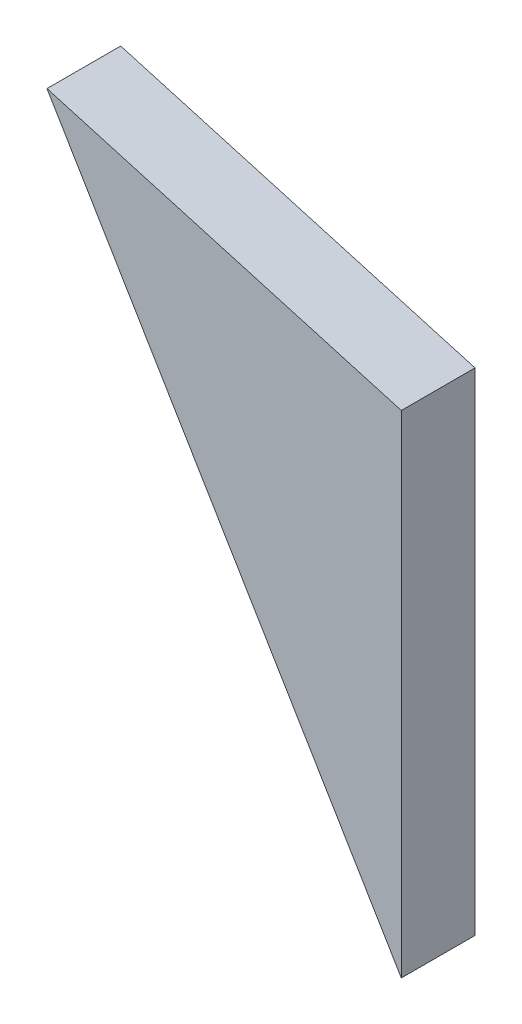
SolidWorks part; units mm, degrees
ref_plane "Front Plane" through (0, 0, 0) normal (0, 0, 1) x (1, 0, 0)
ref_plane "Top Plane" through (0, 0, 0) normal (0, 1, 0) x (1, 0, 0)
ref_plane "Right Plane" through (0, 0, 0) normal (1, 0, 0) x (0, 0, -1)
sketch "Sketch1" plane through (0, 0, 0) normal (0, 0, 1) x (1, 0, 0)
  line L0 (0, 0) -> (0, -20)
  line L1 (0, -20) -> (-14.4189, 4.1346)
  line L2 (-14.4189, 4.1346) -> (0, 0)
  line L3 (0, 0) -> (7.0215, 0) construction
  dimension "D1" = 16
  dimension "D2" = 20
  dimension "D3" = 15
extrude "Boss-Extrude1" add sketch "Sketch1" along normal blind 3
